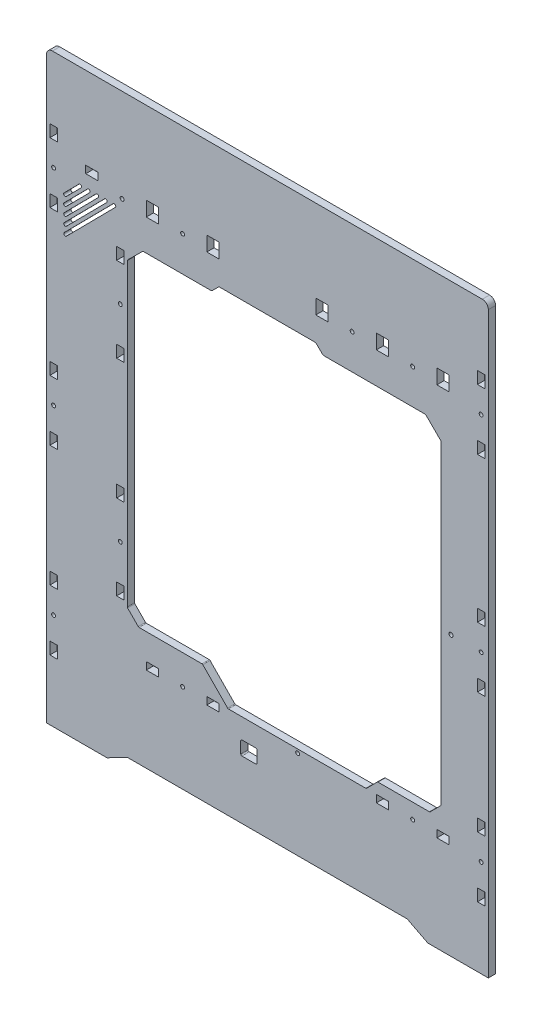
SolidWorks part; units mm, degrees
material "Клен"
ref_plane "Front" through (0, 0, 0) normal (0, 0, 1) x (1, 0, 0)
ref_plane "Top" through (0, 0, 0) normal (0, 1, 0) x (1, 0, 0)
ref_plane "Right" through (0, 0, 0) normal (1, 0, 0) x (0, 0, -1)
sketch "Эскиз1" plane through (0, 0, 0) normal (0, 0, 1) x (1, 0, 0)
  line L2 (738.4043, 525.0072) -> (1158.4308, 525.0072) construction
  line L3 (1133.3665, 477.0072) -> (1133.3665, 520.0072)
  line L4 (1128.3665, 525.0072) -> (773.3665, 525.0072)
  line L5 (768.3665, 520.0072) -> (768.3665, 477.0072)
  line L8 (1124.3665, 292.0072) -> (1130.4665, 292.0072)
  line L9 (1124.3665, 302.0072) -> (1124.3665, 292.0072)
  line L10 (1130.4665, 302.0072) -> (1124.3665, 302.0072)
  line L11 (1130.4665, 292.0072) -> (1130.4665, 302.0072)
  line L32 (1133.3665, 42.0072) -> (1133.3665, 477.0072)
  line L42 (768.3665, 477.0072) -> (768.3665, 42.0072)
  line L43 (768.3665, 42.0072) -> (818.3665, 42.0072)
  line L44 (818.3665, 42.0072) -> (835.3665, 50.7375)
  line L45 (835.3665, 50.7375) -> (1066.3665, 50.7375)
  line L46 (1066.3665, 50.7375) -> (1083.3665, 42.0072)
  line L47 (1083.3665, 42.0072) -> (1133.3665, 42.0072)
  line L48 (1124.3665, 242.0072) -> (1130.4665, 242.0072)
  line L49 (1124.3665, 252.0072) -> (1124.3665, 242.0072)
  line L50 (1130.4665, 252.0072) -> (1124.3665, 252.0072)
  line L51 (1130.4665, 242.0072) -> (1130.4665, 252.0072)
  line L56 (1124.3665, 142.0072) -> (1130.4665, 142.0072)
  line L57 (1124.3665, 152.0072) -> (1124.3665, 142.0072)
  line L58 (1130.4665, 152.0072) -> (1124.3665, 152.0072)
  line L59 (1130.4665, 142.0072) -> (1130.4665, 152.0072)
  line L64 (1124.3665, 92.0072) -> (1130.4665, 92.0072)
  line L65 (1124.3665, 102.0072) -> (1124.3665, 92.0072)
  line L66 (1130.4665, 102.0072) -> (1124.3665, 102.0072)
  line L67 (1130.4665, 92.0072) -> (1130.4665, 102.0072)
  line L72 (1100.8665, 127.1049) -> (1090.8665, 127.1049)
  line L73 (1100.8665, 121.0049) -> (1100.8665, 127.1049)
  line L74 (1090.8665, 121.0049) -> (1100.8665, 121.0049)
  line L75 (1090.8665, 127.1049) -> (1090.8665, 121.0049)
  line L80 (1050.8665, 127.1049) -> (1040.8665, 127.1049)
  line L81 (1050.8665, 121.0049) -> (1050.8665, 127.1049)
  line L82 (1040.8665, 121.0049) -> (1050.8665, 121.0049)
  line L83 (1040.8665, 127.1049) -> (1040.8665, 121.0049)
  line L88 (941.3665, 110.5049) -> (929.8665, 110.5049)
  line L89 (942.3665, 100.0049) -> (942.3665, 109.5049)
  line L90 (929.8665, 99.0049) -> (941.3665, 99.0049)
  line L91 (928.8665, 109.5049) -> (928.8665, 100.0049)
  line L96 (910.8665, 121.0049) -> (910.8665, 127.1049)
  line L97 (900.8665, 121.0049) -> (910.8665, 121.0049)
  line L98 (900.8665, 127.1049) -> (900.8665, 121.0049)
  line L99 (910.8665, 127.1049) -> (900.8665, 127.1049)
  line L104 (860.8665, 121.0049) -> (860.8665, 127.1049)
  line L105 (850.8665, 121.0049) -> (860.8665, 121.0049)
  line L106 (850.8665, 127.1049) -> (850.8665, 121.0049)
  line L107 (860.8665, 127.1049) -> (850.8665, 127.1049)
  line L112 (771.2665, 102.0072) -> (771.2665, 92.0072)
  line L113 (777.3665, 102.0072) -> (771.2665, 102.0072)
  line L114 (777.3665, 92.0072) -> (777.3665, 102.0072)
  line L115 (771.2665, 92.0072) -> (777.3665, 92.0072)
  line L120 (771.2665, 152.0072) -> (771.2665, 142.0072)
  line L121 (777.3665, 152.0072) -> (771.2665, 152.0072)
  line L122 (777.3665, 142.0072) -> (777.3665, 152.0072)
  line L123 (771.2665, 142.0072) -> (777.3665, 142.0072)
  line L128 (826.3665, 171.8072) -> (826.3665, 161.8072)
  line L129 (832.4665, 171.8072) -> (826.3665, 171.8072)
  line L130 (832.4665, 161.8072) -> (832.4665, 171.8072)
  line L131 (826.3665, 161.8072) -> (832.4665, 161.8072)
  line L136 (826.3665, 241.8072) -> (826.3665, 231.8072)
  line L137 (832.4665, 241.8072) -> (826.3665, 241.8072)
  line L138 (832.4665, 231.8072) -> (832.4665, 241.8072)
  line L139 (826.3665, 231.8072) -> (832.4665, 231.8072)
  line L144 (771.2665, 252.0072) -> (771.2665, 242.0072)
  line L145 (777.3665, 252.0072) -> (771.2665, 252.0072)
  line L146 (777.3665, 242.0072) -> (777.3665, 252.0072)
  line L147 (771.2665, 242.0072) -> (777.3665, 242.0072)
  line L152 (1124.3665, 412.0072) -> (1130.4665, 412.0072)
  line L153 (1124.3665, 422.0072) -> (1124.3665, 412.0072)
  line L154 (1130.4665, 422.0072) -> (1124.3665, 422.0072)
  line L155 (1130.4665, 412.0072) -> (1130.4665, 422.0072)
  line L160 (1124.3665, 462.0072) -> (1130.4665, 462.0072)
  line L161 (1124.3665, 472.0072) -> (1124.3665, 462.0072)
  line L162 (1130.4665, 472.0072) -> (1124.3665, 472.0072)
  line L163 (1130.4665, 462.0072) -> (1130.4665, 472.0072)
  line L168 (1090.8665, 457.1072) -> (1090.8665, 445.0072)
  line L169 (1100.8665, 457.1072) -> (1090.8665, 457.1072)
  line L170 (1100.8665, 445.0072) -> (1100.8665, 457.1072)
  line L171 (1090.8665, 445.0072) -> (1100.8665, 445.0072)
  line L176 (1040.8665, 457.1072) -> (1040.8665, 445.0072)
  line L177 (1050.8665, 457.1072) -> (1040.8665, 457.1072)
  line L178 (1050.8665, 445.0072) -> (1050.8665, 457.1072)
  line L179 (1040.8665, 445.0072) -> (1050.8665, 445.0072)
  line L184 (990.8665, 457.1072) -> (990.8665, 445.0072)
  line L185 (1000.8665, 457.1072) -> (990.8665, 457.1072)
  line L186 (1000.8665, 445.0072) -> (1000.8665, 457.1072)
  line L187 (990.8665, 445.0072) -> (1000.8665, 445.0072)
  line L192 (900.8665, 445.0072) -> (910.8665, 445.0072)
  line L193 (900.8665, 457.1072) -> (900.8665, 445.0072)
  line L194 (910.8665, 457.1072) -> (900.8665, 457.1072)
  line L195 (910.8665, 445.0072) -> (910.8665, 457.1072)
  line L200 (826.3665, 411.8072) -> (826.3665, 401.8072)
  line L201 (832.4665, 411.8072) -> (826.3665, 411.8072)
  line L202 (832.4665, 401.8072) -> (832.4665, 411.8072)
  line L203 (826.3665, 401.8072) -> (832.4665, 401.8072)
  line L224 (996.2808, 419.7551) -> (991.4523, 424.5835)
  line L225 (1081.1223, 419.1693) -> (997.695, 419.1693)
  line L226 (1094.1201, 406.6723) -> (1081.8269, 418.8789)
  line L227 (1094.4155, 146.42) -> (1094.4155, 405.9627)
  line L228 (1085.3572, 136.8536) -> (1094.1263, 145.7167)
  line L229 (1042.289, 136.5569) -> (1084.6463, 136.5569)
  line L230 (1032.8134, 127.4016) -> (1041.5781, 136.2603)
  line L231 (918.729, 127.1049) -> (1032.1025, 127.1049)
  line L232 (897.5745, 148.2016) -> (918.0158, 127.4039)
  line L233 (844.9385, 148.5006) -> (896.8613, 148.5006)
  line L234 (835.4584, 157.6604) -> (844.2276, 148.7973)
  line L235 (835.1693, 405.9627) -> (835.1693, 158.3637)
  line L236 (847.7579, 418.8789) -> (835.4647, 406.6723)
  line L237 (904.0381, 419.1693) -> (848.4625, 419.1693)
  line L238 (910.2808, 424.5835) -> (905.4523, 419.7551)
  line L239 (990.0381, 425.1693) -> (911.695, 425.1693)
  line L240 (850.8665, 445.0072) -> (860.8665, 445.0072)
  line L241 (850.8665, 457.1072) -> (850.8665, 445.0072)
  line L242 (860.8665, 457.1072) -> (850.8665, 457.1072)
  line L243 (860.8665, 445.0072) -> (860.8665, 457.1072)
  line L244 (784.8721, 398.2711) -> (825.3055, 439.1538)
  line L245 (823.528, 440.9118) -> (783.0946, 400.0291)
  line L248 (784.8331, 405.3421) -> (818.2346, 439.1147)
  line L249 (816.4571, 440.8727) -> (783.0556, 407.1001)
  line L252 (784.794, 412.4131) -> (811.1636, 439.0757)
  line L253 (809.3861, 440.8336) -> (783.0165, 414.171)
  line L256 (784.7549, 419.484) -> (804.0927, 439.0366)
  line L257 (802.3151, 440.7946) -> (782.9774, 421.242)
  line L260 (784.7159, 426.555) -> (797.0217, 438.9975)
  line L261 (795.2442, 440.7555) -> (782.9384, 428.313)
  line L268 (771.2665, 422.0072) -> (771.2665, 412.0072)
  line L269 (777.3665, 422.0072) -> (771.2665, 422.0072)
  line L270 (777.3665, 412.0072) -> (777.3665, 422.0072)
  line L271 (771.2665, 412.0072) -> (777.3665, 412.0072)
  line L276 (800.8665, 451.0072) -> (810.8665, 451.0072)
  line L277 (800.8665, 457.1072) -> (800.8665, 451.0072)
  line L278 (810.8665, 457.1072) -> (800.8665, 457.1072)
  line L279 (810.8665, 451.0072) -> (810.8665, 457.1072)
  line L284 (771.2665, 472.0072) -> (771.2665, 462.0072)
  line L285 (777.3665, 472.0072) -> (771.2665, 472.0072)
  line L286 (777.3665, 462.0072) -> (777.3665, 472.0072)
  line L287 (771.2665, 462.0072) -> (777.3665, 462.0072)
  line L292 (826.3665, 341.8072) -> (826.3665, 331.8072)
  line L293 (832.4665, 341.8072) -> (826.3665, 341.8072)
  line L294 (832.4665, 331.8072) -> (832.4665, 341.8072)
  line L295 (826.3665, 331.8072) -> (832.4665, 331.8072)
  line L300 (771.2665, 302.0072) -> (771.2665, 292.0072)
  line L301 (777.3665, 302.0072) -> (771.2665, 302.0072)
  line L302 (777.3665, 292.0072) -> (777.3665, 302.0072)
  line L303 (771.2665, 292.0072) -> (777.3665, 292.0072)
  arc A1 (1133.3665, 520.0072) -> (1128.3665, 525.0072) centre (1128.3665, 520.0072) ccw
  circle A2 centre (1127.4165, 272.0072) radius 1.6
  arc A3 (773.3665, 525.0072) -> (768.3665, 520.0072) centre (773.3665, 520.0072) ccw
  circle A4 centre (1102.521, 272.0072) radius 1.7
  circle A6 centre (1127.4165, 122.0072) radius 1.6
  circle A24 centre (1070.8665, 124.0549) radius 1.6
  circle A26 centre (975.8665, 124.0549) radius 1.6
  circle A28 centre (880.8665, 124.0549) radius 1.6
  arc A34 (929.8665, 110.5049) -> (928.8665, 109.5049) centre (929.8665, 109.5049) ccw
  arc A35 (942.3665, 109.5049) -> (941.3665, 110.5049) centre (941.3665, 109.5049) ccw
  arc A36 (941.3665, 99.0049) -> (942.3665, 100.0049) centre (941.3665, 100.0049) ccw
  arc A37 (928.8665, 100.0049) -> (929.8665, 99.0049) centre (929.8665, 100.0049) ccw
  circle A38 centre (774.3165, 122.0072) radius 1.6
  circle A40 centre (829.4165, 202.0072) radius 1.6
  circle A42 centre (774.3165, 272.0072) radius 1.6
  circle A44 centre (1127.4165, 442.0072) radius 1.6
  circle A46 centre (1070.8665, 448.0572) radius 1.6
  circle A48 centre (1020.8665, 448.0572) radius 1.6
  circle A50 centre (880.8665, 448.0572) radius 1.6
  circle A52 centre (830.8665, 448.0572) radius 1.6
  arc A56 (825.3055, 439.1538) -> (823.528, 440.9118) centre (824.4168, 440.0328) ccw
  arc A57 (783.0946, 400.0291) -> (784.8721, 398.2711) centre (783.9834, 399.1501) ccw
  arc A60 (818.2346, 439.1147) -> (816.4571, 440.8727) centre (817.3458, 439.9937) ccw
  arc A61 (783.0556, 407.1001) -> (784.8331, 405.3421) centre (783.9443, 406.2211) ccw
  arc A64 (811.1636, 439.0757) -> (809.3861, 440.8336) centre (810.2749, 439.9546) ccw
  arc A65 (783.0165, 414.171) -> (784.794, 412.4131) centre (783.9053, 413.292) ccw
  arc A82 (991.4523, 424.5835) -> (990.0381, 425.1693) centre (990.0381, 423.1693) ccw
  arc A83 (996.2808, 419.7551) -> (997.695, 419.1693) centre (997.695, 421.1693) ccw
  arc A84 (1081.8269, 418.8789) -> (1081.1223, 419.1693) centre (1081.1223, 418.1693) ccw
  arc A85 (1094.4155, 405.9627) -> (1094.1201, 406.6723) centre (1093.4155, 405.9627) ccw
  arc A86 (1094.1263, 145.7167) -> (1094.4155, 146.42) centre (1093.4155, 146.42) ccw
  arc A87 (1084.6463, 136.5569) -> (1085.3572, 136.8536) centre (1084.6463, 137.5569) ccw
  arc A88 (1042.289, 136.5569) -> (1041.5781, 136.2603) centre (1042.289, 135.5569) ccw
  arc A89 (1032.1025, 127.1049) -> (1032.8134, 127.4016) centre (1032.1025, 128.1049) ccw
  arc A90 (918.0158, 127.4039) -> (918.729, 127.1049) centre (918.729, 128.1049) ccw
  arc A91 (897.5745, 148.2016) -> (896.8613, 148.5006) centre (896.8613, 147.5006) ccw
  arc A92 (844.2276, 148.7973) -> (844.9385, 148.5006) centre (844.9385, 149.5006) ccw
  arc A93 (835.1693, 158.3637) -> (835.4584, 157.6604) centre (836.1693, 158.3637) ccw
  arc A94 (835.4647, 406.6723) -> (835.1693, 405.9627) centre (836.1693, 405.9627) ccw
  arc A95 (848.4625, 419.1693) -> (847.7579, 418.8789) centre (848.4625, 418.1693) ccw
  arc A96 (904.0381, 419.1693) -> (905.4523, 419.7551) centre (904.0381, 421.1693) ccw
  arc A97 (911.695, 425.1693) -> (910.2808, 424.5835) centre (911.695, 423.1693) ccw
  arc A100 (804.0927, 439.0366) -> (802.3151, 440.7946) centre (803.2039, 439.9156) ccw
  arc A101 (782.9774, 421.242) -> (784.7549, 419.484) centre (783.8662, 420.363) ccw
  arc A104 (797.0217, 438.9975) -> (795.2442, 440.7555) centre (796.1329, 439.8765) ccw
  arc A105 (782.9384, 428.313) -> (784.7159, 426.555) centre (783.8271, 427.434) ccw
  circle A106 centre (774.3165, 442.0072) radius 1.6
  circle A108 centre (829.4165, 372.0072) radius 1.6
  point P10 (1133.3665, 525.0072)
  point P14 (768.3665, 525.0072)
  dimension "D1" = 5
  dimension "D2" = 113.2
  dimension "D3" = 60
  dimension "D4" = 90
  dimension "D5" = 60
extrude "Бобышка-Вытянуть1" add sketch "Эскиз1" along normal blind 6
